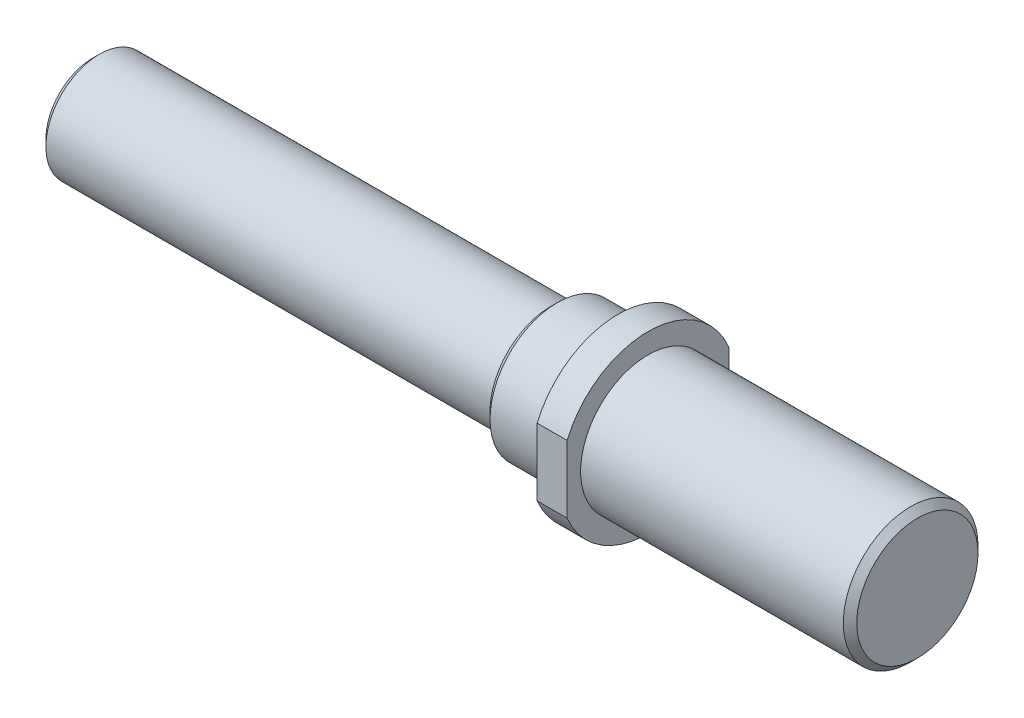
SolidWorks part; units mm, degrees
ref_plane "Front Plane" through (0, 0, 0) normal (0, 0, 1) x (1, 0, 0)
ref_plane "Top Plane" through (0, 0, 0) normal (0, 1, 0) x (1, 0, 0)
ref_plane "Right Plane" through (0, 0, 0) normal (1, 0, 0) x (0, 0, -1)
sketch "Sketch1" plane through (0, 0, 0) normal (1, 0, 0) x (0, 0, -1)
  line L0 (0, 0) -> (0, 42.1801) construction
  line L1 (0, 0) -> (-29.4966, 0) construction
  circle A0 centre (0, 0) radius 7
  dimension "D1" = 14
extrude "Boss-Extrude1" add sketch "Sketch1" against normal blind 41.225 and the other way blind 20
sketch "Sketch2" plane through (0, 0, 0) normal (1, 0, 0) x (0, 0, -1)
  circle A0 centre (0, 0) radius 3.9688
  circle A1 centre (0, 0) radius 7
  circle A2 centre (0, 0) radius 7 construction
  dimension "D1" = 7.9375
extrude "Cut-Extrude1" cut sketch "Sketch2" against normal through all from offset 7.225 offset against normal yes
sketch "Sketch3" plane through (-7.225, 0, 0) normal (-1, 0, 0) x (0, 0, 1)
  circle A0 centre (0, 0) radius 5
  circle A1 centre (0, 0) radius 7
  circle A2 centre (0, 0) radius 7 construction
  dimension "D1" = 10
extrude "Cut-Extrude2" cut sketch "Sketch3" against normal blind 5
sketch "Sketch4" plane through (-2.225, 0, 0) normal (-1, 0, 0) x (0, 0, 1)
  circle A0 centre (0, 0) radius 6.5
  circle A1 centre (0, 0) radius 7
  circle A2 centre (0, 0) radius 7 construction
  dimension "D1" = 13
extrude "Cut-Extrude3" cut sketch "Sketch4" against normal through all
sketch "Sketch5" plane through (20, 0, 0) normal (1, 0, 0) x (0, 0, -1)
  circle A0 centre (0, 0) radius 5
  circle A1 centre (0, 0) radius 6.5
  circle A3 centre (0, 0) radius 6.5 construction
  dimension "D1" = 10
extrude "Cut-Extrude4" cut sketch "Sketch5" against normal blind 20
chamfer "Chamfer1" distance 0.5 angle 45 3 edges at (-7.225, 0, 5) (-41.225, 0, -3.9688) (20, 0, -5)
sketch "Sketch6" plane through (0, 0, 0) normal (1, 0, 0) x (0, 0, -1)
  line L0 (0, -8.1329) -> (0, 9.3804) construction
  line L1 (-6, -2.5) -> (-6, 2.5)
  line L2 (0, 6.9282) -> (-6, 3.4641) construction
  line L3 (-6, 3.4641) -> (-6, -3.4641) construction
  line L4 (-6, -3.4641) -> (0, -6.9282) construction
  line L5 (0, -6.9282) -> (6, -3.4641) construction
  line L6 (6, -3.4641) -> (6, 3.4641) construction
  line L7 (6, 3.4641) -> (0, 6.9282) construction
  line L8 (6, 2.5) -> (6, -2.5)
  circle A0 centre (0, 0) radius 6 construction
  circle A1 centre (0, 0) radius 6.5 construction
  arc A2 (-6, 2.5) -> (-6, -2.5) centre (0, 0) ccw
  arc A3 (6, -2.5) -> (6, 2.5) centre (0, 0) ccw
  dimension "D1" = 12
extrude "Cut-Extrude5" cut sketch "Sketch6" against normal through all
